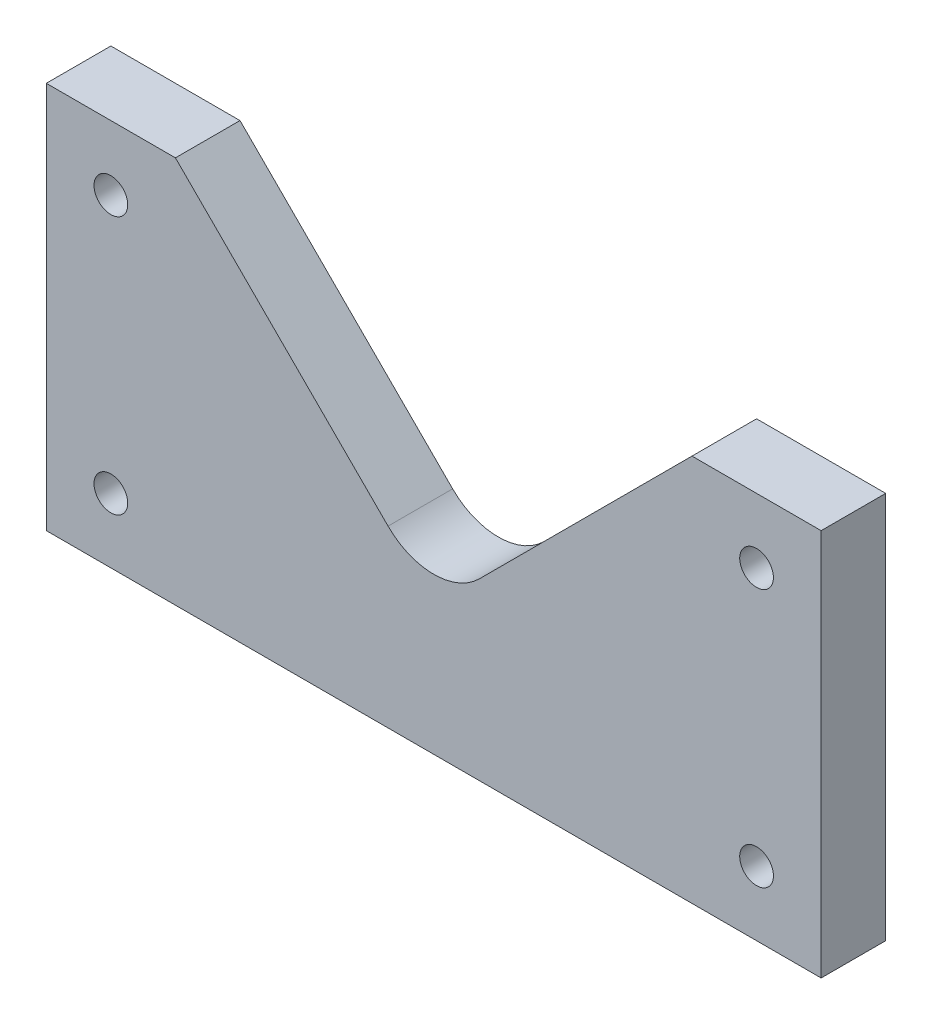
SolidWorks part; units mm, degrees
ref_plane "Front Plane" through (0, 0, 0) normal (0, 0, 1) x (1, 0, 0)
ref_plane "Top Plane" through (0, 0, 0) normal (0, 1, 0) x (1, 0, 0)
ref_plane "Right Plane" through (0, 0, 0) normal (1, 0, 0) x (0, 0, -1)
sketch "Sketch1" plane through (0, 0, 0) normal (0, 0, 1) x (1, 0, 0)
  line L1 (-76.2, 50.8) -> (76.2, 50.8)
  line L2 (-76.2, 50.8) -> (-76.2, -50.8)
  line L3 (-76.2, -50.8) -> (76.2, -50.8)
  line L4 (76.2, 50.8) -> (76.2, -50.8)
  line L5 (-76.2, 50.8) -> (76.2, -50.8) construction
  line L6 (-76.2, -50.8) -> (76.2, 50.8) construction
  point P0 (0, 0)
  dimension "D1" = 152.4
  dimension "D2" = 101.6
extrude "Boss-Extrude1" add sketch "Sketch1" along normal mid plane 12.7
sketch "Sketch2" plane through (0, 0, 6.35) normal (0, 0, 1) x (1, 0, 0)
  line L0 (0, 0) -> (50.8, 50.8)
  line L1 (76.2, 50.8) -> (-76.2, 50.8) construction
  line L2 (50.8, 50.8) -> (-50.8, 50.8)
  line L3 (-50.8, 50.8) -> (0, 0)
extrude "Cut-Extrude1" cut sketch "Sketch2" against normal through all
sketch "Sketch3" plane through (0, 0, 6.35) normal (0, 0, 1) x (1, 0, 0)
  line L0 (76.2, -50.8) -> (76.2, 50.8) construction
  line L1 (-76.2, -50.8) -> (76.2, -50.8)
  line L2 (-76.2, -50.8) -> (-76.2, -25.4)
  line L3 (-76.2, -25.4) -> (76.2, -25.4)
  line L4 (76.2, -50.8) -> (76.2, -25.4)
  dimension "D1" = 25.4
extrude "Cut-Extrude2" cut sketch "Sketch3" against normal through all
hole_wizard "G (0.261) Diameter Hole1" positions "Sketch4" profile "Sketch5" hole size "G" standard "ANSI Inch" end condition up to next
sketch "Sketch4" plane through (0, 0, 6.35) normal (0, 0, 1) x (1, 0, 0)
  line L0 (-50.8, 50.8) -> (-76.2, 50.8) construction
  line L1 (-76.2, 50.8) -> (-76.2, -25.4) construction
  point P0 (-63.5, 38.1)
  point P2 (-63.5, -12.7)
  point P4 (63.5, -12.7)
  point P6 (63.5, 38.1)
  dimension "D1" = 12.7
  dimension "D2" = 50.8
  dimension "D3" = 12.7
  dimension "D4" = 127
sketch "Sketch5" plane through (-63.5, 38.1, 6.35) normal (1, 0, 0) x (0, -1, 0)
  line L0 (0, 0) -> (0, 12.7)
  line L1 (0, 12.7) -> (3.3147, 12.7)
  line L2 (3.3147, 12.7) -> (3.3147, 0)
  line L5 (3.3147, 0) -> (0, 0)
  line L11 (0, -6.35) -> (0, 107.95) construction
  dimension "Thru Hole Dia." = 6.6294
  dimension "Thru Hole Depth" = 12.7
fillet "Fillet1" radius 12.7 1 edges at (0, 0, 0)
